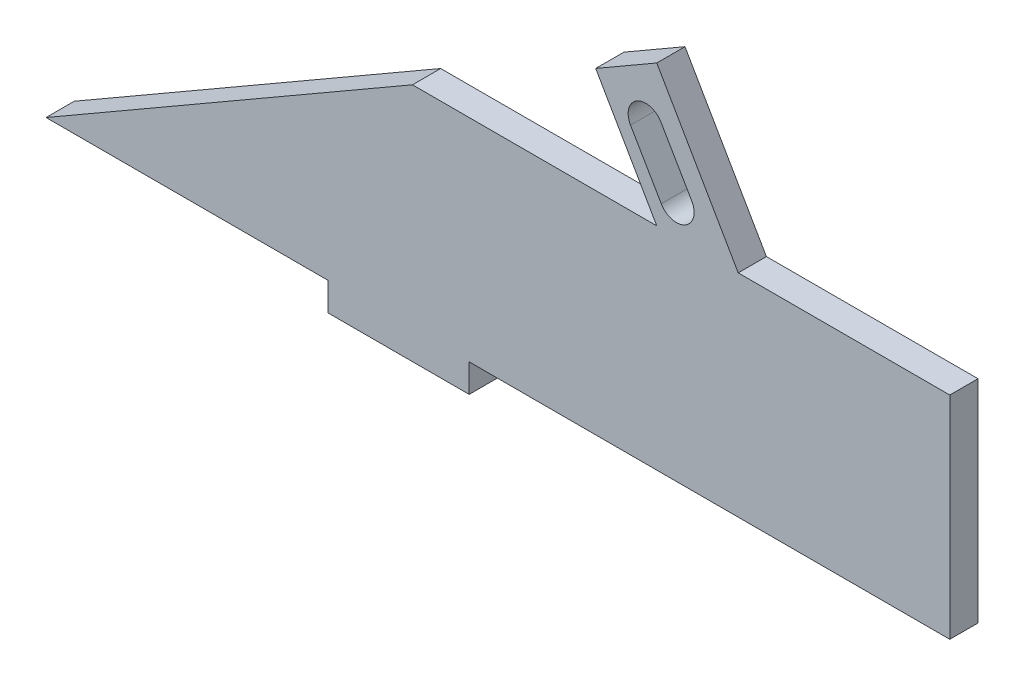
SolidWorks part; units mm, degrees
ref_plane "Front Plane" through (0, 0, 0) normal (0, 0, 1) x (1, 0, 0)
ref_plane "Top Plane" through (0, 0, 0) normal (0, 1, 0) x (1, 0, 0)
ref_plane "Right Plane" through (0, 0, 0) normal (1, 0, 0) x (0, 0, -1)
sketch "Sketch1" plane through (0, 0, 0) normal (0, 0, 1) x (1, 0, 0)
  line L0 (0, 0) -> (-38.1495, 0)
  line L1 (-98.1495, 0) -> (-46.188, 30)
  line L2 (-46.188, 30) -> (-11.547, 30)
  line L3 (-11.547, 30) -> (-20.2073, 45)
  line L4 (-20.2073, 45) -> (-11.547, 50)
  line L5 (-11.547, 50) -> (0, 30)
  line L6 (0, 30) -> (0, 0)
  line L7 (-58.1495, 0) -> (-58.1495, -4)
  line L8 (-58.1495, -4) -> (-38.1495, -4)
  line L9 (-38.1495, -4) -> (-38.1495, 0)
  line L10 (-58.1495, 0) -> (-98.1495, 0)
  dimension "D1" = 30
  dimension "D2" = 60
  dimension "D3" = 23.094
  dimension "D4" = 10
  dimension "D5" = 34.641
  dimension "D6" = 30
  dimension "D7" = 20
  dimension "D8" = 4
  dimension "D9" = 40
extrude "Boss-Extrude1" add sketch "Sketch1" along normal blind 4
sketch "Sketch3" plane through (0, 0, 4) normal (0, 0, 1) x (1, 0, 0)
  line L0 (-11.547, 50) -> (-20.2073, 45) construction
  line L1 (-6.5935, 35.5515) -> (-10.9504, 43.0254)
  line L2 (-10.9131, 33.0334) -> (-15.27, 40.5073)
  arc A0 (-10.9131, 33.0334) -> (-6.5935, 35.5515) centre (-8.7533, 34.2924) ccw
  arc A1 (-10.9504, 43.0254) -> (-15.27, 40.5073) centre (-13.1102, 41.7664) ccw
  dimension "D1" = 5
  dimension "D2" = 15
extrude "Cut-Extrude2" cut sketch "Sketch3" against normal blind 4
sketch "Sketch5" plane through (0, 0, 0) normal (1, 0, 0) x (0, 0, -1)
  line L0 (-4, 30) -> (0, 30)
  line L1 (0, 30) -> (0, 0)
  line L2 (0, 0) -> (-4, 0)
  line L3 (-4, 0) -> (-4, 30)
extrude "Boss-Extrude2" add sketch "Sketch5" along normal blind 30
